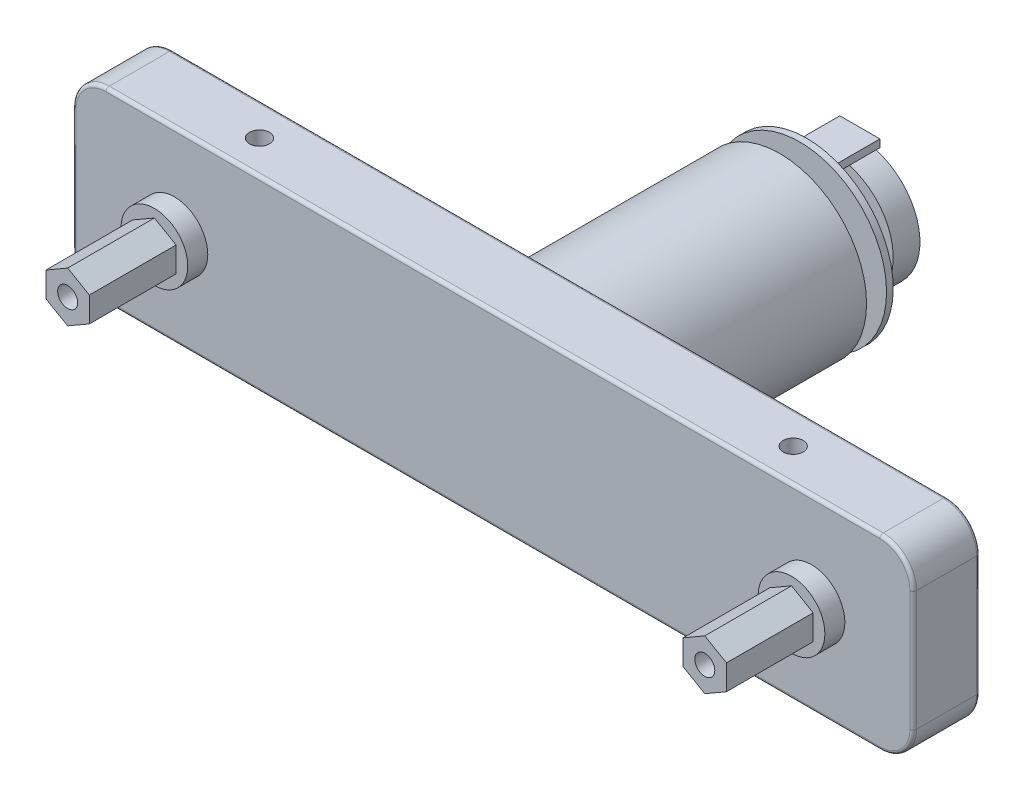
SolidWorks part; units mm, degrees
ref_plane "前视基准面" through (0, 0, 0) normal (0, 0, 1) x (1, 0, 0)
ref_plane "上视基准面" through (0, 0, 0) normal (0, 1, 0) x (1, 0, 0)
ref_plane "右视基准面" through (0, 0, 0) normal (1, 0, 0) x (0, 0, -1)
sketch "草图1" plane through (0, 0, 0) normal (0, 0, 1) x (1, 0, 0)
  line L1 (-63, 14) -> (63, 14)
  line L2 (-63, 14) -> (-63, -14)
  line L3 (-63, -14) -> (63, -14)
  line L4 (63, 14) -> (63, -14)
  line L5 (-63, 14) -> (63, -14) construction
  line L6 (-63, -14) -> (63, 14) construction
  point P0 (0, 0)
  dimension "D1" = 126
  dimension "D2" = 28
extrude "凸台-拉伸1" add sketch "草图1" along normal mid plane 10
fillet "圆角1" radius 5 4 edges at (-63, -14, 0) (-63, 14, 0) (63, -14, 0) (63, 14, 0)
fillet "圆角2" radius 0.5 16 edges at (61.5355, -12.5355, -5) (63, 0, -5) (61.5355, 12.5355, -5) (0, 14, -5) (-61.5355, 12.5355, -5) (-63, 0, -5) (-61.5355, -12.5355, -5) (0, -14, -5) (-61.5355, 12.5355, 5) (0, 14, 5) (61.5355, 12.5355, 5) (63, 0, 5) (61.5355, -12.5355, 5) (0, -14, 5) (-61.5355, -12.5355, 5) (-63, 0, 5)
sketch "草图3" plane through (0, -14, 0) normal (0, -1, 0) x (1, 0, 0)
  line L0 (0, -4.5) -> (0, 4.5) construction
  line L1 (-58, -4.5) -> (58, -4.5) construction
  line L2 (58, 4.5) -> (-58, 4.5) construction
  circle A0 centre (-40, 0) radius 1.5
  circle A1 centre (40, 0) radius 1.5
  dimension "D1" = 3
  dimension "D2" = 40
extrude "切除-拉伸1" cut sketch "草图3" against normal blind 10
sketch "草图4" plane through (0, 0, 5) normal (0, 0, 1) x (1, 0, 0)
  circle A0 centre (47.75, 0) radius 5
  dimension "D1" = 10
  dimension "D2" = 47.75
extrude "凸台-拉伸2" add sketch "草图4" along normal blind 3
sketch "草图5" plane through (0, 0, 8) normal (0, 0, 1) x (1, 0, 0)
  line L1 (47.75, -3.7528) -> (51, -1.8764)
  line L2 (51, -1.8764) -> (51, 1.8764)
  line L3 (51, 1.8764) -> (47.75, 3.7528)
  line L4 (47.75, 3.7528) -> (44.5, 1.8764)
  line L5 (44.5, 1.8764) -> (44.5, -1.8764)
  line L6 (44.5, -1.8764) -> (47.75, -3.7528)
  circle A0 centre (47.75, 0) radius 3.25 construction
  dimension "D1" = 6.5
extrude "凸台-拉伸3" add sketch "草图5" along normal blind 13
sketch "草图6" plane through (0, 0, 21) normal (0, 0, 1) x (1, 0, 0)
  circle A0 centre (47.75, 0) radius 1.5
  dimension "D1" = 3
extrude "切除-拉伸2" cut sketch "草图6" against normal blind 6
mirror "镜向1" about plane through (0, 0, 0) normal (1, 0, 0) of "凸台-拉伸2", "切除-拉伸2", "凸台-拉伸3"
sketch "草图7" plane through (0, 0, -5) normal (0, 0, -1) x (-1, 0, 0)
  circle A0 centre (0, 0) radius 13
  dimension "D1" = 26
extrude "凸台-拉伸4" add sketch "草图7" along normal blind 33
sketch "草图8" plane through (0, 0, -38) normal (0, 0, -1) x (-1, 0, 0)
  circle A0 centre (0, 0) radius 5
  dimension "D1" = 10
extrude "凸台-拉伸5" add sketch "草图8" along normal blind 3
sketch "草图9" plane through (0, 0, -41) normal (0, 0, -1) x (-1, 0, 0)
  circle A0 centre (0, 0) radius 13 construction
  circle A1 centre (0, 0) radius 13
extrude "凸台-拉伸6" add sketch "草图9" along normal blind 1
sketch "草图10" plane through (0, 0, -42) normal (0, 0, -1) x (-1, 0, 0)
  circle A0 centre (0, 0) radius 1
  dimension "D1" = 2
extrude "凸台-拉伸7" add sketch "草图10" along normal blind 4
sketch "草图11" plane through (0, 0, -46) normal (0, 0, -1) x (-1, 0, 0)
  circle A0 centre (0, 0) radius 9
  dimension "D1" = 18
extrude "凸台-拉伸8" add sketch "草图11" along normal blind 4
sketch "草图12" plane through (0, 0, -42) normal (0, 0, -1) x (-1, 0, 0)
  line L1 (-3, 10.396) -> (3, 10.396)
  line L2 (-3, 10.396) -> (-3, 9.2498)
  line L3 (-3, 9.2498) -> (3, 9.2498)
  line L4 (3, 10.396) -> (3, 9.2498)
  dimension "D1" = 6
  dimension "D2" = 3
extrude "凸台-拉伸9" add sketch "草图12" along normal blind 8
sketch "草图13" plane through (0, 0, -42) normal (0, 0, -1) x (-1, 0, 0)
  line L1 (-6.3754, -6.1855) -> (6.6246, -6.1855)
  line L2 (-6.3754, -6.1855) -> (-6.3754, -11.1855)
  line L3 (-6.3754, -11.1855) -> (6.6246, -11.1855)
  line L4 (6.6246, -6.1855) -> (6.6246, -11.1855)
  circle A0 centre (0, 0) radius 13 construction
  dimension "D1" = 13
  dimension "D2" = 5
extrude "凸台-拉伸10" add sketch "草图13" along normal blind 3.9
mirror "镜向2" about plane through (0, 0, 0) normal (0, 1, 0) of "切除-拉伸1"
